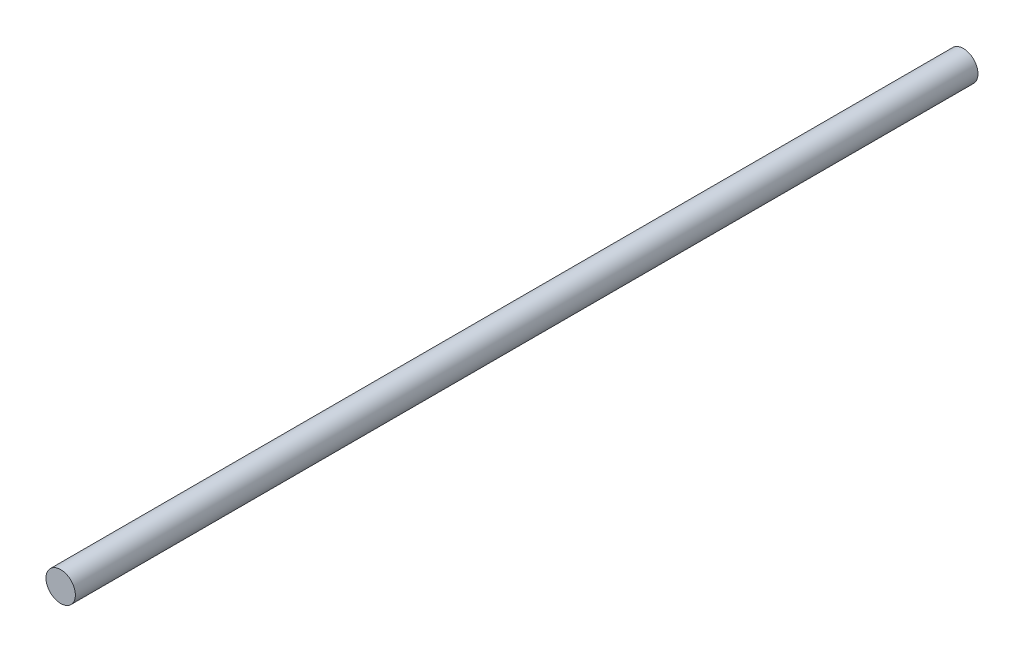
SolidWorks part; units mm, degrees
ref_plane "Front Plane" through (0, 0, 0) normal (1, 0, 0) x (0, 1, 0)
ref_plane "Top Plane" through (0, 0, 0) normal (0, 0, 1) x (0, 1, 0)
ref_plane "Right Plane" through (0, 0, 0) normal (0, 1, 0) x (-1, 0, 0)
sketch "Sketch1" plane through (0, 0, 0) normal (0, 0, 1) x (0, 1, 0)
  circle A0 centre (0, 0) radius 2.5
  dimension "D1" = 5
extrude "Boss-Extrude1" add sketch "Sketch1" along normal blind 153.5
